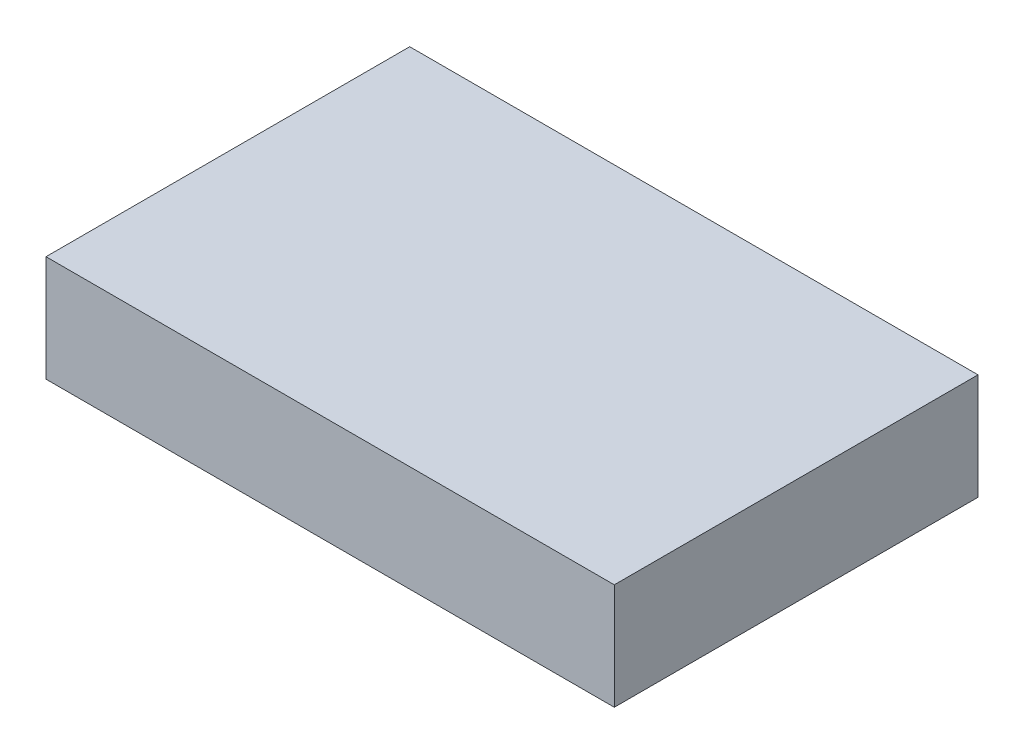
SolidWorks part; units mm, degrees
ref_plane "前视基准面" through (0, 0, 0) normal (0, 0, 1) x (1, 0, 0)
ref_plane "上视基准面" through (0, 0, 0) normal (0, 1, 0) x (1, 0, 0)
ref_plane "右视基准面" through (0, 0, 0) normal (1, 0, 0) x (0, 0, -1)
sketch "Sketch1" plane through (0, 0, 0) normal (0, 1, 0) x (1, 0, 0)
  line L1 (-37.5, 24) -> (37.5, 24)
  line L2 (-37.5, 24) -> (-37.5, -24)
  line L3 (-37.5, -24) -> (37.5, -24)
  line L4 (37.5, 24) -> (37.5, -24)
  line L5 (-37.5, 24) -> (37.5, -24) construction
  line L6 (-37.5, -24) -> (37.5, 24) construction
  point P0 (0, 0)
  dimension "D1" = 75
  dimension "D2" = 48
extrude "Boss-Extrude1" add sketch "Sketch1" along normal blind 14
